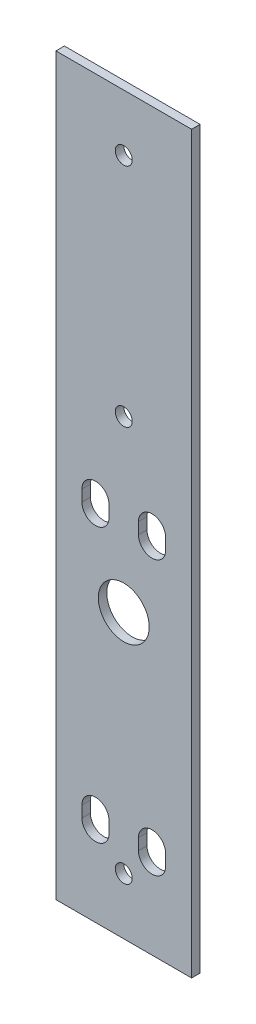
SolidWorks part; units mm, degrees
ref_plane "前视基准面" through (0, 0, 0) normal (0, 0, 1) x (1, 0, 0)
ref_plane "上视基准面" through (0, 0, 0) normal (0, 1, 0) x (1, 0, 0)
ref_plane "右视基准面" through (0, 0, 0) normal (1, 0, 0) x (0, 0, -1)
sketch "草图1" plane through (0, 0, 0) normal (0, 0, 1) x (1, 0, 0)
  line L1 (12, 65) -> (-12, 65)
  line L3 (12, -65) -> (-12, -65)
  line L4 (-12, 65) -> (-12, -65)
  line L5 (0, -65) -> (0, 65) construction
  line L6 (7.5, 0) -> (-12, 0) construction
  line L11 (12, 65) -> (12, -65)
  line L12 (-5, -1.8) -> (-5, 0.2) construction
  line L13 (5, -49.2) -> (-5, -49.2) construction
  line L14 (5, -49.2) -> (5, -0.8) construction
  line L15 (5, -0.8) -> (-5, -0.8) construction
  line L16 (-5, -49.2) -> (-5, -0.8) construction
  line L17 (0, -0.8) -> (0, -49.2) construction
  line L18 (5, -25) -> (-5, -25) construction
  line L19 (3.9, 2) -> (6.1, 2) construction
  line L20 (3.9, 2) -> (3.9, 1.2) construction
  line L21 (3.9, 1.2) -> (6.1, 1.2) construction
  line L22 (6.1, 2) -> (6.1, 1.2) construction
  line L23 (5, 1.2) -> (5, 2) construction
  line L24 (3.9, 1.6) -> (6.1, 1.6) construction
  line L25 (-7.4, -1.8) -> (-7.4, 0.2)
  line L26 (-2.6, -1.8) -> (-2.6, 0.2)
  line L27 (5, -1.8) -> (5, 0.2) construction
  line L28 (7.4, -1.8) -> (7.4, 0.2)
  line L29 (2.6, -1.8) -> (2.6, 0.2)
  line L30 (-5, -48.2) -> (-5, -50.2) construction
  line L31 (-7.4, -48.2) -> (-7.4, -50.2)
  line L32 (-2.6, -48.2) -> (-2.6, -50.2)
  line L33 (5, -48.2) -> (5, -50.2) construction
  line L34 (7.4, -48.2) -> (7.4, -50.2)
  line L35 (2.6, -48.2) -> (2.6, -50.2)
  circle A0 centre (0, 15) radius 1.5
  circle A2 centre (0, -55) radius 1.5
  circle A3 centre (0, 55) radius 1.5
  circle A4 centre (-5, -0.8) radius 2.4 construction
  circle A5 centre (5, -0.8) radius 2.4 construction
  circle A6 centre (5, -49.2) radius 2.4 construction
  circle A7 centre (-5, -49.2) radius 2.4 construction
  circle A8 centre (0, -15) radius 4.5
  arc A9 (-7.4, -1.8) -> (-2.6, -1.8) centre (-5, -1.8) ccw
  arc A10 (-2.6, 0.2) -> (-7.4, 0.2) centre (-5, 0.2) ccw
  arc A11 (7.4, -1.8) -> (2.6, -1.8) centre (5, -1.8) cw
  arc A12 (2.6, 0.2) -> (7.4, 0.2) centre (5, 0.2) cw
  arc A13 (-7.4, -48.2) -> (-2.6, -48.2) centre (-5, -48.2) cw
  arc A14 (-2.6, -50.2) -> (-7.4, -50.2) centre (-5, -50.2) cw
  arc A15 (7.4, -48.2) -> (2.6, -48.2) centre (5, -48.2) ccw
  arc A16 (2.6, -50.2) -> (7.4, -50.2) centre (5, -50.2) ccw
  point P0 (0, 0)
  point P12 (0, -25)
  point P20 (5, 1.6)
  point P26 (-5, -0.8)
  point P33 (5, -0.8)
  point P40 (-5, -49.2)
  point P47 (5, -49.2)
  dimension "D3" = 3
  dimension "D5" = 40
  dimension "D6" = 3
  dimension "D1" = 10
  dimension "D4" = 2.2
  dimension "D10" = 9
  dimension "D12" = 4.8
  dimension "D14" = 50
  dimension "D16" = 2.8
  dimension "D2" = 24
  dimension "D7" = 40
  dimension "D8" = 10
  dimension "D9" = 48.4
  dimension "D17" = 17
  dimension "D18" = 2
extrude "凸台-拉伸1" add sketch "草图1" along normal blind 1.5
sketch "草图4" plane through (0, 0, 1.5) normal (0, 0, 1) x (1, 0, 0)
  line L0 (0.295, -14.0445) -> (0.295, -13.5445)
  line L9 (-0.295, -14.0445) -> (-0.295, -13.5445)
  line L12 (-0.295, -13.5445) -> (0.295, -13.5445)
  line L14 (0, -15) -> (0, -13.5445) construction
  line L15 (-0.0315, -15) -> (0, -15) construction
  arc A1 (-0.295, -14.0445) -> (0.295, -14.0445) centre (0, -15) ccw
  dimension "D2" = 0.5
  dimension "D1" = 0.59
